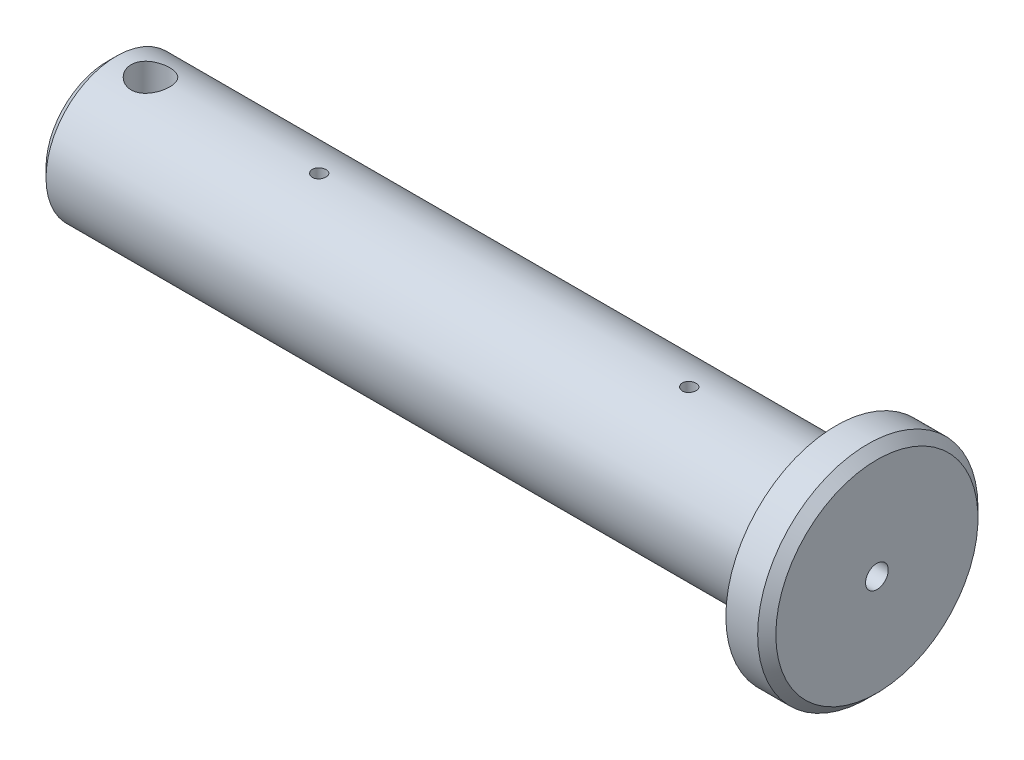
SolidWorks part; units mm, degrees
material "AISI 1045 Aço, trefilado"
ref_plane "Plano frontal" through (0, 0, 0) normal (0, 0, 1) x (1, 0, 0)
ref_plane "Plano superior" through (0, 0, 0) normal (0, 1, 0) x (1, 0, 0)
ref_plane "Plano direito" through (0, 0, 0) normal (1, 0, 0) x (0, 0, -1)
sketch "Esboço1" plane through (0, 0, 0) normal (0, 0, 1) x (1, 0, 0)
  line L0 (-84.69, 0) -> (84.69, 0) construction
  line L1 (84.69, 2.5) -> (84.69, 22.25)
  line L2 (82.69, 24.25) -> (75.69, 24.25)
  line L3 (75.69, 24.25) -> (75.69, 15.5)
  line L4 (75.69, 15.5) -> (-82.69, 15.5)
  line L5 (-84.69, 13.5) -> (-84.69, 0)
  line L6 (-82.69, 15.5) -> (-84.69, 13.5)
  line L7 (84.69, 22.25) -> (82.69, 24.25)
  line L8 (84.69, 2.5) -> (74.69, 2.5)
  line L9 (74.69, 2.5) -> (74.0891, 1.5)
  line L10 (74.0891, 1.5) -> (-43.7887, 1.5)
  line L11 (-43.7887, 1.5) -> (-44.69, 0)
  line L12 (-84.69, 0) -> (-44.69, 0)
  point P4 (84.69, 24.25)
  point P7 (-84.69, 15.5)
  dimension "D1" = 48.5
  dimension "D2" = 31
  dimension "D3" = 169.38
  dimension "D4" = 9
  dimension "D5" = 59
  dimension "D6" = 40
  dimension "D9" = 3
  dimension "D10" = 59
  dimension "D11" = 10
  dimension "D12" = 5
revolve "Revolução1" add sketch "Esboço1" angle 360 about L0
cosmetic thread "Representação de rosca1" parameters "D2"=6
sketch "Esboço2" plane through (0, 0, 0) normal (0, 1, 0) x (1, 0, 0)
  line L0 (84.69, 0) -> (43.39, 0) construction
  line L1 (84.69, -22.25) -> (84.69, 22.25) construction
  line L2 (43.39, 0) -> (-16.3511, 0) construction
  line L3 (-16.3511, 0) -> (-38.05, 0) construction
  line L4 (-38.05, 0) -> (-75.19, 0) construction
  circle A0 centre (43.39, 0) radius 1.5
  circle A1 centre (-38.05, 0) radius 1.5
  dimension "D2" = 3
  dimension "D3" = 122.74
  dimension "D1" = 41.3
extrude "Corte-extrusão1" cut sketch "Esboço2" along normal through all
sketch "Esboço3" plane through (0, 0, 0) normal (0, 1, 0) x (1, 0, 0)
  line L0 (-84.69, 0) -> (-75.19, 0) construction
  line L1 (-84.69, 13.5) -> (-84.69, -13.5) construction
  circle A0 centre (-75.19, 0) radius 4.25
  dimension "D1" = 8.5
  dimension "D2" = 9.5
extrude "Corte-extrusão2" cut sketch "Esboço3" against normal through all both and the other way through all
